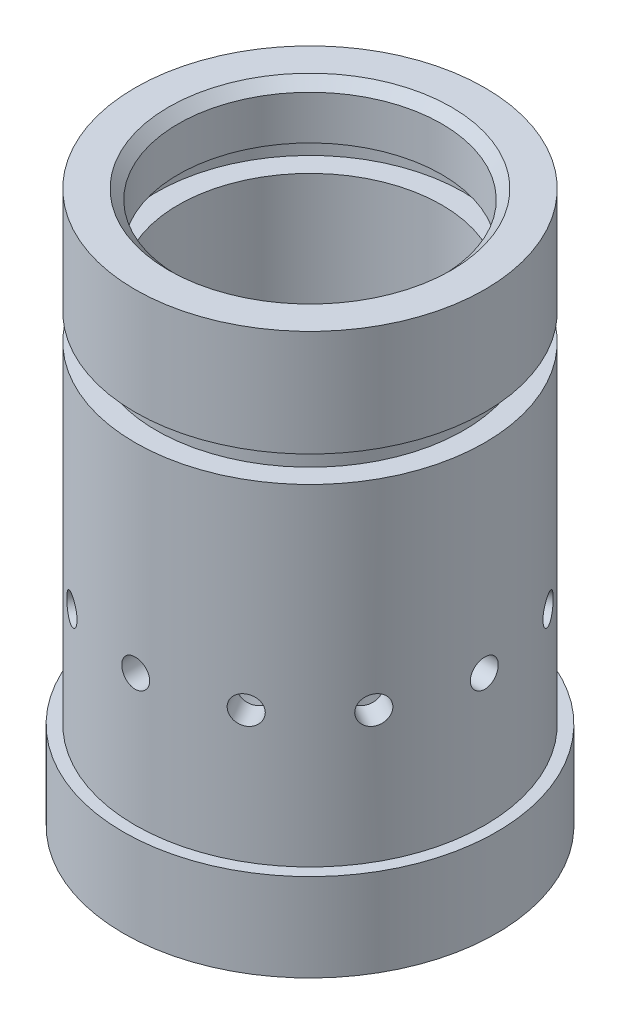
SolidWorks part; units mm, degrees
material "6061 Alloy"
ref_plane "Front Plane" through (0, 0, 0) normal (0, 0, 1) x (1, 0, 0)
ref_plane "Top Plane" through (0, 0, 0) normal (0, 1, 0) x (1, 0, 0)
ref_plane "Right Plane" through (0, 0, 0) normal (1, 0, 0) x (0, 0, -1)
sketch "Sketch1" plane through (0, 0, 0) normal (0, 0, 1) x (1, 0, 0)
  line L0 (0, 0) -> (0, 10.9165) construction
  line L1 (19.05, -60.8471) -> (19.05, -19.1911)
  line L2 (19.05, -19.1911) -> (20.447, -17.7941)
  line L3 (20.447, -17.7941) -> (25.2857, -17.7941)
  line L6 (25.2857, -17.7941) -> (25.2857, -60.8471)
  line L7 (25.2857, -60.8471) -> (19.05, -60.8471)
  line L8 (19.05, -60.8471) -> (15.875, -60.8471)
  line L9 (15.875, -60.8471) -> (25.7175, -97.5798)
  line L11 (25.7175, -97.5798) -> (26.9875, -97.5798)
  line L13 (15.875, -60.8471) -> (7.9375, -31.2239) construction
  line L14 (26.9875, -84.8798) -> (26.9875, -97.5798)
  line L15 (25.2857, -60.8471) -> (25.2857, -84.8798)
  line L16 (-26.9875, -84.8798) -> (26.9875, -84.8798) construction
  line L17 (25.2857, -84.8798) -> (26.9875, -84.8798)
  line L18 (-26.9875, -84.8798) -> (-26.9875, -97.5798)
  line L19 (-26.9875, -97.5798) -> (26.9875, -97.5798) construction
  line L20 (-22.2123, -17.7941) -> (22.2123, -17.7941) construction
  line L21 (19.05, -25.5411) -> (22.225, -25.5411)
  line L22 (25.2857, -33.1611) -> (22.225, -33.1611)
  line L23 (25.2857, -33.1611) -> (25.2857, -36.9711)
  line L24 (25.2857, -36.9711) -> (22.225, -36.9711)
  line L25 (22.225, -33.1611) -> (22.225, -36.9711)
  line L26 (19.05, -25.5411) -> (19.05, -29.3511)
  line L27 (19.05, -29.3511) -> (22.225, -29.3511)
  line L28 (22.225, -25.5411) -> (22.225, -29.3511)
  line L29 (-25.7175, -97.5798) -> (-26.9875, -97.5798)
  line L30 (-15.875, -60.8471) -> (-25.7175, -97.5798)
  line L31 (-22.225, -25.5411) -> (-22.225, -29.3511)
  line L32 (-19.05, -29.3511) -> (-22.225, -29.3511)
  line L33 (-19.05, -25.5411) -> (-19.05, -29.3511)
  line L34 (-22.225, -33.1611) -> (-22.225, -36.9711)
  line L35 (-25.2857, -36.9711) -> (-22.225, -36.9711)
  line L36 (-25.2857, -33.1611) -> (-25.2857, -36.9711)
  line L37 (-25.2857, -33.1611) -> (-22.225, -33.1611)
  line L38 (-19.05, -25.5411) -> (-22.225, -25.5411)
  line L39 (-25.2857, -84.8798) -> (-26.9875, -84.8798)
  line L40 (-25.2857, -60.8471) -> (-25.2857, -84.8798)
  line L41 (-19.05, -60.8471) -> (-15.875, -60.8471)
  line L42 (-25.2857, -60.8471) -> (-19.05, -60.8471)
  line L43 (-25.2857, -17.7941) -> (-25.2857, -60.8471)
  line L44 (-20.447, -17.7941) -> (-25.2857, -17.7941)
  line L45 (-19.05, -19.1911) -> (-20.447, -17.7941)
  line L46 (-19.05, -60.8471) -> (-19.05, -19.1911)
  point P26 (25.2857, -17.7941)
  point P37 (15.875, -60.8471)
  point P53 (-15.875, -60.8471)
  point P54 (-25.2857, -17.7941)
  dimension "D1" = 44.45
  dimension "D2" = 3.81
  dimension "D3" = 44.45
  dimension "D4" = 3.81
  dimension "D5" = 19.05
  dimension "D6" = 45
  dimension "D7" = 1.397
  dimension "D8" = 3.0607
  dimension "D9" = 6.35
revolve "Revolve1" add sketch "Sketch1" angle 360 about L0
ref_plane "Plane1" through (0, 0, -25.2857) normal (0, 0, -1) x (-1, 0, 0)
sketch "Sketch2" plane through (0, 0, -25.2857) normal (0, 0, -1) x (-1, 0, 0)
  point P0 (0, -65.8298)
hole_wizard "#10-32 Tapped Hole1" positions "Sketch2" profile "Sketch3" tap size "#10-32" standard "ANSI Inch"
sketch "Sketch3" plane through (0, -65.8298, -25.2857) normal (1, 0, 0) x (0, 1, 0)
  line L0 (0, 0) -> (0, 4.1661)
  line L1 (0, 4.1661) -> (2.0193, 3.81)
  line L2 (2.0193, 3.81) -> (2.0193, 0)
  line L5 (2.0193, 0) -> (0, 0)
  line L10 (0, 4.1661) -> (-2.0193, 3.81) construction
  line L11 (0, -6.35) -> (0, 107.95) construction
  dimension "Tap Drill Dia." = 4.0386
  dimension "Tap Drill Depth" = 3.81
  dimension "Drill Angle" = 160
pattern_circular "CirPattern1" count 12 over 360 about axis through (0, 0, 0) along (0, -1, 0) of "#10-32 Tapped Hole1"
